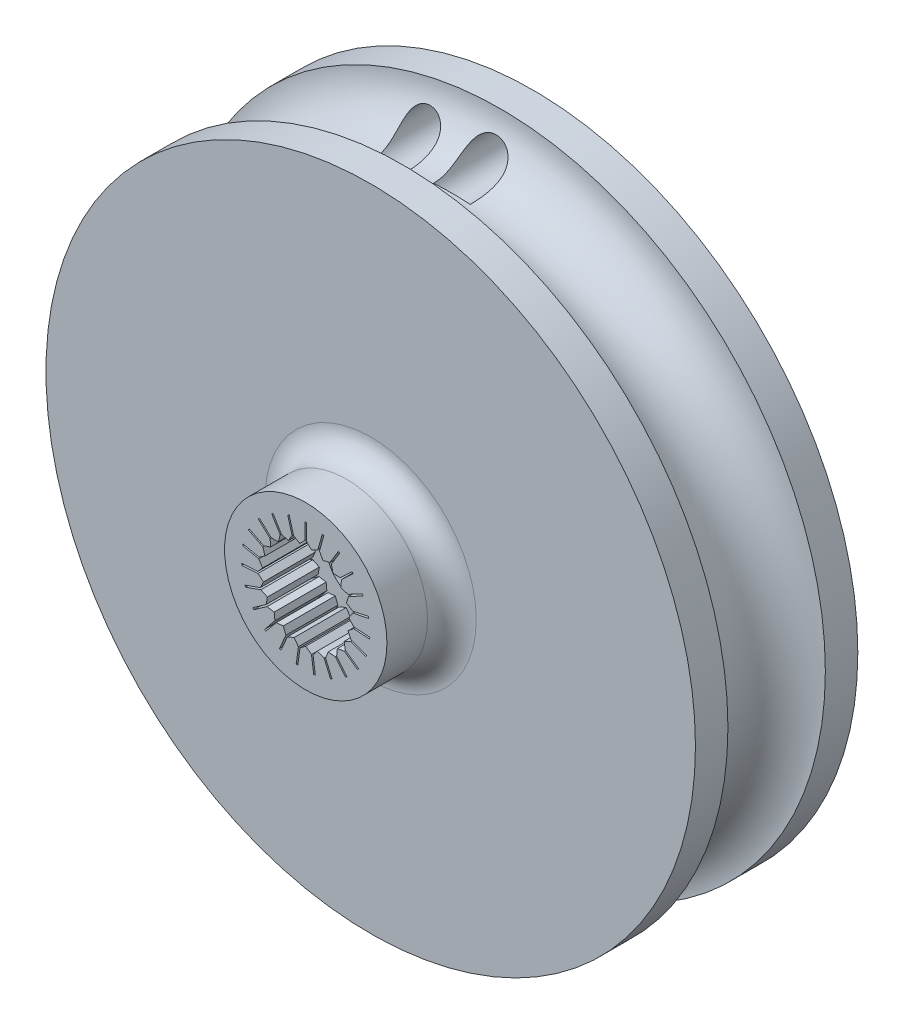
SolidWorks part; units mm, degrees
ref_plane "正面" through (0, 0, 0) normal (0, 0, 1) x (1, 0, 0)
ref_plane "平面" through (0, 0, 0) normal (0, 1, 0) x (1, 0, 0)
ref_plane "右側面" through (0, 0, 0) normal (1, 0, 0) x (0, 0, -1)
sketch "ｽｹｯﾁ8" plane through (0, 0, 0) normal (0, 1, 0) x (1, 0, 0)
  line L0 (0, 0) -> (0, 10)
  line L1 (0, 10) -> (20, 10)
  line L2 (20, 10) -> (20, 8)
  line L3 (0, 0) -> (20, 0)
  line L4 (20, 0) -> (20, 2)
  arc A0 (20, 2) -> (20, 8) centre (20, 5) cw
  point P8 (29.5562, 7.5217)
  point P9 (0, 0)
  point P10 (29.0892, 8.0318)
  point P11 (30.4879, 5)
  dimension "D4" = 3
  dimension "D1" = 20
  dimension "D2" = 2
  dimension "D3" = 10
revolve "回転1" add sketch "ｽｹｯﾁ8" angle 360 about L0
sketch "ｽｹｯﾁ6" plane through (0, 0, 0) normal (0, 0, 1) x (1, 0, 0)
  circle A0 centre (0, 0) radius 5
  dimension "D1" = 10
extrude "ﾎﾞｽ - 押し出し3" add sketch "ｽｹｯﾁ6" along normal blind 4
sketch "ｽｹｯﾁ5" plane through (0, 0, 0) normal (0, 0, 1) x (1, 0, 0)
  line L0 (-0.3625, 2.6375) -> (0, 3) construction
  line L1 (0, 3) -> (0.3625, 2.6375) construction
  line L2 (-0.3625, 2.6375) -> (0, 0) construction
  line L3 (0, 0) -> (0.3625, 2.6375) construction
  line L4 (0, 3) -> (0, 0) construction
  line L5 (-0.05, 2.95) -> (-0.05, 3.95)
  line L6 (-0.05, 3.95) -> (0.05, 3.95)
  line L7 (0.05, 3.95) -> (0.05, 2.95)
  line L8 (-0.05, 2.95) -> (0.05, 2.95) construction
  line L9 (-0.3625, 2.6375) -> (-0.05, 2.95)
  line L10 (-0.05, 2.95) -> (0.05, 2.95) construction
  line L11 (0.3625, 2.6375) -> (0.05, 2.95)
  line L12 (0.3625, 2.6375) -> (0.7478, 2.8541)
  line L13 (0.7478, 2.8541) -> (1.0176, 3.817)
  line L14 (1.1138, 3.79) -> (0.844, 2.8271)
  line L15 (1.0607, 2.4419) -> (0.844, 2.8271)
  line L16 (1.0176, 3.817) -> (1.1138, 3.79)
  line L17 (1.0607, 2.4419) -> (1.4901, 2.5465)
  line L18 (1.4901, 2.5465) -> (2.0096, 3.4009)
  line L19 (2.0951, 3.349) -> (1.5755, 2.4946)
  line L20 (1.6801, 2.0652) -> (1.5755, 2.4946)
  line L21 (2.0096, 3.4009) -> (2.0951, 3.349)
  line L22 (1.6801, 2.0652) -> (2.1218, 2.0501)
  line L23 (2.1218, 2.0501) -> (2.8527, 2.7326)
  line L24 (2.9209, 2.6595) -> (2.1901, 1.977)
  line L25 (2.175, 1.5353) -> (2.1901, 1.977)
  line L26 (2.8527, 2.7326) -> (2.9209, 2.6595)
  line L27 (2.175, 1.5353) -> (2.5963, 1.4016)
  line L28 (2.5963, 1.4016) -> (3.4841, 1.8617)
  line L29 (3.5301, 1.7729) -> (2.6423, 1.3128)
  line L30 (2.5086, 0.8915) -> (2.6423, 1.3128)
  line L31 (3.4841, 1.8617) -> (3.5301, 1.7729)
  line L32 (2.5086, 0.8915) -> (2.8781, 0.6491)
  line L33 (2.8781, 0.6491) -> (3.8572, 0.8526)
  line L34 (3.8776, 0.7547) -> (2.8985, 0.5512)
  line L35 (2.6561, 0.1817) -> (2.8985, 0.5512)
  line L36 (3.8572, 0.8526) -> (3.8776, 0.7547)
  line L37 (2.6561, 0.1817) -> (2.9465, -0.1514)
  line L38 (2.9465, -0.1514) -> (3.9442, -0.2197)
  line L39 (3.9374, -0.3194) -> (2.9397, -0.2512)
  line L40 (2.6066, -0.5417) -> (2.9397, -0.2512)
  line L41 (3.9442, -0.2197) -> (3.9374, -0.3194)
  line L42 (2.6066, -0.5417) -> (2.7964, -0.9408)
  line L43 (2.7964, -0.9408) -> (3.7387, -1.2757)
  line L44 (3.7052, -1.3699) -> (2.7629, -1.035)
  line L45 (2.3638, -1.2248) -> (2.7629, -1.035)
  line L46 (3.7387, -1.2757) -> (3.7052, -1.3699)
  line L47 (2.3638, -1.2248) -> (2.4389, -1.6604)
  line L48 (2.4389, -1.6604) -> (3.2559, -2.237)
  line L49 (3.1982, -2.3187) -> (2.3812, -1.7421)
  line L50 (1.9457, -1.8171) -> (2.3812, -1.7421)
  line L51 (3.2559, -2.237) -> (3.1982, -2.3187)
  line L52 (1.9457, -1.8171) -> (1.9005, -2.2568)
  line L53 (1.9005, -2.2568) -> (2.5316, -3.0325)
  line L54 (2.454, -3.0956) -> (1.8229, -2.3199)
  line L55 (1.3833, -2.2747) -> (1.8229, -2.3199)
  line L56 (2.5316, -3.0325) -> (2.454, -3.0956)
  line L57 (1.3833, -2.2747) -> (1.2211, -2.6859)
  line L58 (1.2211, -2.6859) -> (1.6195, -3.6031)
  line L59 (1.5278, -3.6429) -> (1.1294, -2.7257)
  line L60 (0.7183, -2.5636) -> (1.1294, -2.7257)
  line L61 (1.6195, -3.6031) -> (1.5278, -3.6429)
  line L62 (0.7183, -2.5636) -> (0.4512, -2.9157)
  line L63 (0.4512, -2.9157) -> (0.5874, -3.9064)
  line L64 (0.4883, -3.92) -> (0.3522, -2.9293)
  line L65 (0, -2.6623) -> (0.3522, -2.9293)
  line L66 (0.5874, -3.9064) -> (0.4883, -3.92)
  line L67 (0, -2.6623) -> (-0.3522, -2.9293)
  line L68 (-0.3522, -2.9293) -> (-0.4883, -3.92)
  line L69 (-0.5874, -3.9064) -> (-0.4512, -2.9157)
  line L70 (-0.7183, -2.5636) -> (-0.4512, -2.9157)
  line L71 (-0.4883, -3.92) -> (-0.5874, -3.9064)
  line L72 (-0.7183, -2.5636) -> (-1.1294, -2.7257)
  line L73 (-1.1294, -2.7257) -> (-1.5278, -3.6429)
  line L74 (-1.6195, -3.6031) -> (-1.2211, -2.6859)
  line L75 (-1.3833, -2.2747) -> (-1.2211, -2.6859)
  line L76 (-1.5278, -3.6429) -> (-1.6195, -3.6031)
  line L77 (-1.3833, -2.2747) -> (-1.8229, -2.3199)
  line L78 (-1.8229, -2.3199) -> (-2.454, -3.0956)
  line L79 (-2.5316, -3.0325) -> (-1.9005, -2.2568)
  line L80 (-1.9457, -1.8171) -> (-1.9005, -2.2568)
  line L81 (-2.454, -3.0956) -> (-2.5316, -3.0325)
  line L82 (-1.9457, -1.8171) -> (-2.3812, -1.7421)
  line L83 (-2.3812, -1.7421) -> (-3.1982, -2.3187)
  line L84 (-3.2559, -2.237) -> (-2.4389, -1.6604)
  line L85 (-2.3638, -1.2248) -> (-2.4389, -1.6604)
  line L86 (-3.1982, -2.3187) -> (-3.2559, -2.237)
  line L87 (-2.3638, -1.2248) -> (-2.7629, -1.035)
  line L88 (-2.7629, -1.035) -> (-3.7052, -1.3699)
  line L89 (-3.7387, -1.2757) -> (-2.7964, -0.9408)
  line L90 (-2.6066, -0.5417) -> (-2.7964, -0.9408)
  line L91 (-3.7052, -1.3699) -> (-3.7387, -1.2757)
  line L92 (-2.6066, -0.5417) -> (-2.9397, -0.2512)
  line L93 (-2.9397, -0.2512) -> (-3.9374, -0.3194)
  line L94 (-3.9442, -0.2197) -> (-2.9465, -0.1514)
  line L95 (-2.6561, 0.1817) -> (-2.9465, -0.1514)
  line L96 (-3.9374, -0.3194) -> (-3.9442, -0.2197)
  line L97 (-2.6561, 0.1817) -> (-2.8985, 0.5512)
  line L98 (-2.8985, 0.5512) -> (-3.8776, 0.7547)
  line L99 (-3.8572, 0.8526) -> (-2.8781, 0.6491)
  line L100 (-2.5086, 0.8915) -> (-2.8781, 0.6491)
  line L101 (-3.8776, 0.7547) -> (-3.8572, 0.8526)
  line L102 (-2.5086, 0.8915) -> (-2.6423, 1.3128)
  line L103 (-2.6423, 1.3128) -> (-3.5301, 1.7729)
  line L104 (-3.4841, 1.8617) -> (-2.5963, 1.4016)
  line L105 (-2.175, 1.5353) -> (-2.5963, 1.4016)
  line L106 (-3.5301, 1.7729) -> (-3.4841, 1.8617)
  line L107 (-2.175, 1.5353) -> (-2.1901, 1.977)
  line L108 (-2.1901, 1.977) -> (-2.9209, 2.6595)
  line L109 (-2.8527, 2.7326) -> (-2.1218, 2.0501)
  line L110 (-1.6801, 2.0652) -> (-2.1218, 2.0501)
  line L111 (-2.9209, 2.6595) -> (-2.8527, 2.7326)
  line L112 (-1.6801, 2.0652) -> (-1.5755, 2.4946)
  line L113 (-1.5755, 2.4946) -> (-2.0951, 3.349)
  line L114 (-2.0096, 3.4009) -> (-1.4901, 2.5465)
  line L115 (-1.0607, 2.4419) -> (-1.4901, 2.5465)
  line L116 (-2.0951, 3.349) -> (-2.0096, 3.4009)
  line L117 (-1.0607, 2.4419) -> (-0.844, 2.8271)
  line L118 (-0.844, 2.8271) -> (-1.1138, 3.79)
  line L119 (-1.0176, 3.817) -> (-0.7478, 2.8541)
  line L120 (-0.3625, 2.6375) -> (-0.7478, 2.8541)
  line L121 (-1.1138, 3.79) -> (-1.0176, 3.817)
  circle A0 centre (0, 0) radius 3 construction
  circle A1 centre (0, 0) radius 2.6623 construction
  point P147 (0, 0)
  dimension "D1" = 6
  dimension "D2" = 7.826
  dimension "D3" = 7.826
  dimension "D4" = 0.1
  dimension "D5" = 1
  dimension "D6" = 23
extrude "ｶｯﾄ - 押し出し5" cut sketch "ｽｹｯﾁ5" against normal blind 3.2 from surface at 4 starting at face at (5, 0, 4)
fillet "ﾌｨﾚｯﾄ2" radius 1.5 1 edges at (5, 0, 0)
sketch "ｽｹｯﾁ9" plane through (0, 0, -10) normal (0, 0, -1) x (-1, 0, 0)
  circle A0 centre (0, 0) radius 1.9
  dimension "D1" = 3.8
extrude "ｶｯﾄ - 押し出し6" cut sketch "ｽｹｯﾁ9" against normal through all
sketch "ｽｹｯﾁ10" plane through (0, 0, -10) normal (0, 0, -1) x (-1, 0, 0)
  circle A0 centre (0, 0) radius 3
  dimension "D1" = 6
extrude "ｶｯﾄ - 押し出し7" cut sketch "ｽｹｯﾁ10" against normal offset from surface (5.8 mm away) 5 up to face at (1.9, 0, 0.8)
sketch "ｽｹｯﾁ11" plane through (0, 0, -10) normal (0, 0, 1) x (1, 0, 0)
  circle A0 centre (0, 0) radius 17.5 construction
  circle A1 centre (0, 17.5) radius 1.25
  circle A2 centre (-3.9738, 17.0429) radius 1.25
  point P7 (0, 0)
  dimension "D1" = 2.5
  dimension "D2" = 35
  dimension "D3" = 4
extrude "ｶｯﾄ - 押し出し8" cut sketch "ｽｹｯﾁ11" along normal blind 5 contours A1 | A2
equation "\"18.4.300mm\"= 18.3"
equation "\"D2@ｽｹｯﾁ5\"=360deg/46"
equation "\"D3@ｽｹｯﾁ5\"=\"D2@ｽｹｯﾁ5\""
